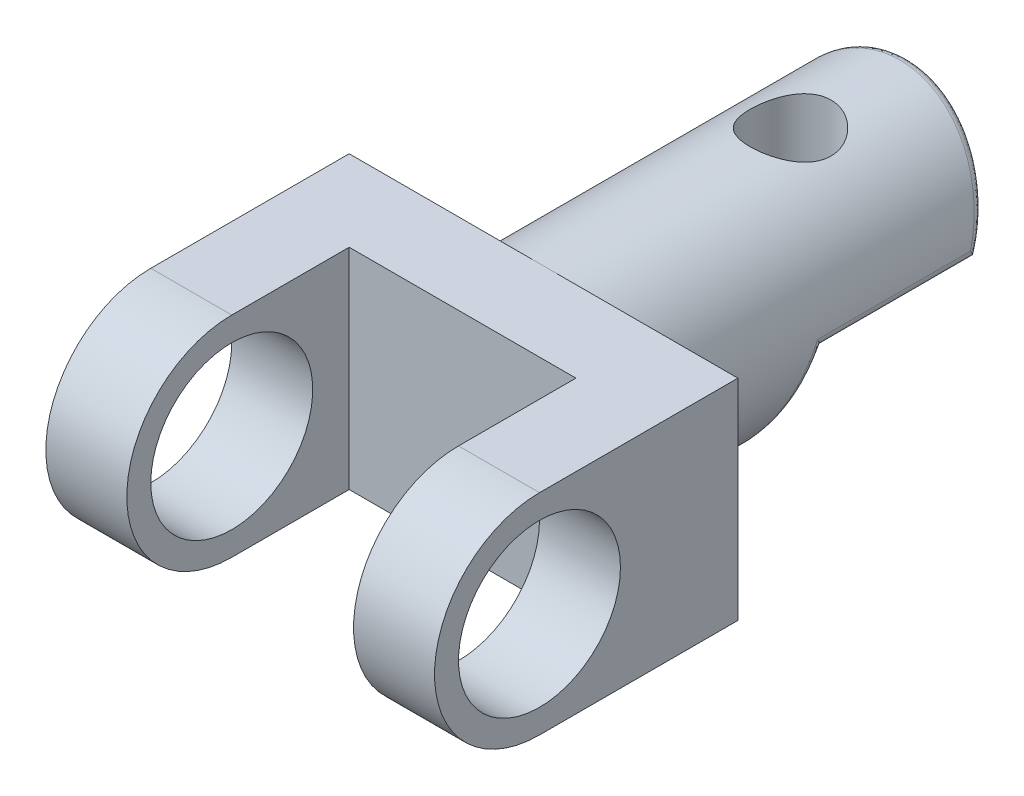
SolidWorks part; units mm, degrees
ref_plane "前视基准面" through (0, 0, 0) normal (0, 0, 1) x (1, 0, 0)
ref_plane "上视基准面" through (0, 0, 0) normal (0, 1, 0) x (1, 0, 0)
ref_plane "右视基准面" through (0, 0, 0) normal (1, 0, 0) x (0, 0, -1)
ref_plane "基准面4" through (0, -42.25, 0) normal (0, 1, 0) x (1, 0, 0)
sketch "草图1" plane through (0, -42.25, 0) normal (0, 1, 0) x (1, 0, 0)
  line L0 (57.25, -53) -> (57.25, -58.375)
  line L1 (57.25, -47) -> (60.4896, -47)
  line L2 (57.25, -47) -> (57.25, -58.375)
  line L3 (57.25, -58.375) -> (60.4896, -58.375)
  line L4 (60.4896, -47) -> (60.4896, -58.375)
  line L6 (60.2396, -53) -> (54.2604, -53) construction
  line L7 (60.4896, -52.8674) -> (60.4896, -48.0923) construction
  dimension "D1" = 47
  dimension "D2" = 11.375
revolve "旋转1" add sketch "草图1" angle 360 about L2
sketch "草图2" plane through (0, 0, 0) normal (1, 0, 0) x (0, 0, -1)
  line L1 (-48.25, -42.25) -> (-53, -42.25) construction
  line L2 (-47, -39) -> (-48.25, -42.25) construction
  line L5 (-53, -42.25) -> (-54.875, -45.5) construction
  line L7 (-48.25, -42.25) -> (-53, -42.25)
  line L8 (-47, -39) -> (-48.25, -42.25)
  line L11 (-53, -42.25) -> (-54.875, -45.5)
  line L12 (-47, -39) -> (-45.9559, -39)
  line L13 (-40.375, -39) -> (-46.8283, -39) construction
  line L14 (-45.9559, -39) -> (-45.9559, -45.5)
  line L15 (-49.5001, -45.5) -> (-40.375, -45.5) construction
  line L16 (-45.9559, -45.5) -> (-54.875, -45.5)
extrude "切除-拉伸1" cut sketch "草图2" against normal through all both and the other way through all
fillet "圆角1" radius 0.25 4 edges at (54.0104, -42.25, 50.625) (60.4896, -42.25, 50.625) (57.25, -39.0104, 47.004) (57.25, -45.4896, 54.869)
sketch "草图4" plane through (0, -42.25, 0) normal (0, -1, 0) x (1, 0, 0)
  line L0 (57.25, 50.75) -> (57.25, 53)
  line L1 (60.2396, 53) -> (54.2604, 53) construction
  circle A0 centre (57.25, 50.75) radius 1.25 construction
  circle A1 centre (57.25, 50.75) radius 1.25
extrude "切除-拉伸2" cut sketch "草图4" against normal through all
ref_plane "基准面5" through (57.25, 0, 0) normal (1, 0, 0) x (0, 0, -1)
sketch "草图5" plane through (57.25, 0, 0) normal (1, 0, 0) x (0, 0, -1)
  line L0 (-52.25, -42.25) -> (-64.5, -42.25) construction
  line L1 (-52.25, -45.4896) -> (-64.5, -45.4896)
  line L2 (-52.25, -39.0104) -> (-64.5, -39.0104)
  line L5 (-58.375, -39.0104) -> (-58.375, -45.4896) construction
  line L6 (-51.9999, -39.0104) -> (-58.375, -39.0104) construction
  line L7 (-58.375, -39.0104) -> (-58.375, -45.4896)
  arc A0 (-52.25, -45.4896) -> (-52.25, -39.0104) centre (-52.25, -42.25) ccw
  arc A1 (-64.5, -39.0104) -> (-64.5, -45.4896) centre (-64.5, -42.25) ccw
  circle A2 centre (-64.5, -42.25) radius 2.5
  point P2 (-58.375, -42.25)
  dimension "D2" = 5
  dimension "D1" = 6.125
extrude "凸台-拉伸1" add sketch "草图5" along normal mid plane 12
sketch "草图6" plane through (0, 0, 0) normal (0, 1, 0) x (1, 0, 0)
  line L0 (57.25, -58.375) -> (57.25, -60.875) construction
  line L1 (53.75, -60.875) -> (60.75, -60.875)
  line L2 (53.75, -60.875) -> (53.75, -74.5108)
  line L3 (53.75, -74.5108) -> (60.75, -74.5108)
  line L4 (60.75, -60.875) -> (60.75, -74.5108)
  dimension "D1" = 7
  dimension "D2" = 2.5
extrude "切除-拉伸3" cut sketch "草图6" against normal through all
